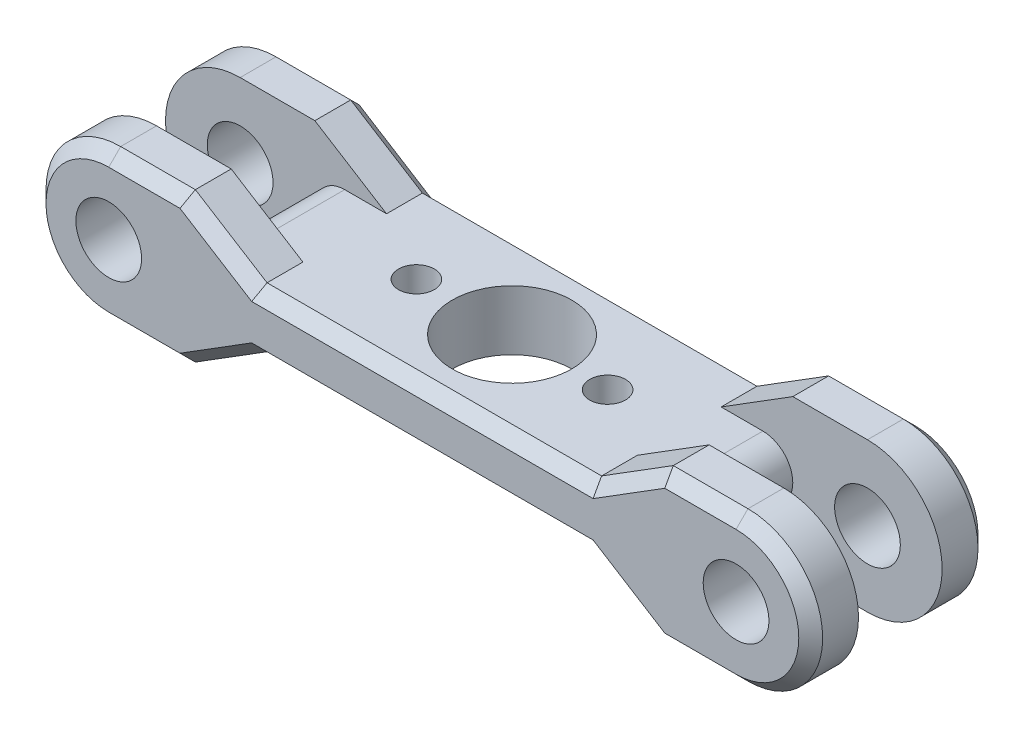
SolidWorks part; units mm, degrees
ref_plane "前视基准面" through (0, 0, 0) normal (0, 0, 1) x (1, 0, 0)
ref_plane "上视基准面" through (0, 0, 0) normal (0, 1, 0) x (1, 0, 0)
ref_plane "右视基准面" through (0, 0, 0) normal (1, 0, 0) x (0, 0, -1)
other "Configuration Table"
sketch "草图1" plane through (0, 0, 0) normal (0, 1, 0) x (1, 0, 0)
  line L1 (-20, -7.5) -> (20, -7.5)
  line L2 (-20, -7.5) -> (-20, 7.5)
  line L3 (-20, 7.5) -> (20, 7.5)
  line L4 (20, -7.5) -> (20, 7.5)
  line L5 (-20, -7.5) -> (20, 7.5) construction
  line L6 (-20, 7.5) -> (20, -7.5) construction
  point P0 (0, 0)
  dimension "D1" = 40
  dimension "D2" = 15
extrude "凸台-拉伸1" add sketch "草图1" along normal blind 5
sketch "草图2" plane through (0, 0, 0) normal (0, 1, 0) x (1, 0, 0)
  line L0 (-8, 0) -> (8, 0) construction
  circle A0 centre (0, 0) radius 5
  circle A1 centre (8, 0) radius 1.5
  circle A2 centre (-8, 0) radius 1.5
  point P5 (0, 0)
  dimension "D1" = 10
  dimension "D2" = 3
  dimension "D3" = 3
  dimension "D4" = 16
extrude "切除-拉伸1" cut sketch "草图2" against normal up to surface (5 mm away) from surface at 5 up to face at (0, 0, 0) starting at face at (0, 5, 0)
sketch "草图6" plane through (0, 0, 0) normal (0, 1, 0) x (1, 0, 0)
  line L0 (0, 7.5) -> (0, -7.5) construction
  line L1 (20, 7.5) -> (32.5, 7.5)
  line L2 (20, 7.5) -> (20, 3.5)
  line L3 (20, 3.5) -> (32.5, 3.5)
  line L4 (32.5, 7.5) -> (32.5, 3.5)
  line L5 (20, -7.5) -> (32.5, -7.5)
  line L6 (20, -7.5) -> (20, -3.5)
  line L7 (20, -3.5) -> (32.5, -3.5)
  line L8 (32.5, -7.5) -> (32.5, -3.5)
  line L9 (20, 7.5) -> (-20, 7.5) construction
  line L10 (-20, -7.5) -> (20, -7.5) construction
  line L11 (-20, -3.5) -> (-32.5, -3.5)
  line L12 (-32.5, -7.5) -> (-32.5, -3.5)
  line L13 (-20, -7.5) -> (-32.5, -7.5)
  line L14 (-20, -7.5) -> (-20, -3.5)
  line L15 (-20, 3.5) -> (-32.5, 3.5)
  line L16 (-32.5, 7.5) -> (-32.5, 3.5)
  line L17 (-20, 7.5) -> (-32.5, 7.5)
  line L18 (-20, 7.5) -> (-20, 3.5)
  dimension "D1" = 4
  dimension "D2" = 4
  dimension "D3" = 12.5
  dimension "D4" = 12.5
extrude "凸台-拉伸3" add sketch "草图6" along normal blind 8.75 and the other way blind 3.75
sketch "草图8" plane through (0, 0, 0) normal (0, 0, 1) x (1, 0, 0)
  line L0 (-20, -3.75) -> (-14, 0)
  line L1 (-20, 0) -> (20, 0) construction
  line L2 (-20, 8.75) -> (-14, 5)
  line L3 (-20, 5) -> (20, 5) construction
  line L4 (-14, 5) -> (-20, 5)
  line L5 (-20, 5) -> (-20, 8.75)
  line L6 (-20, -3.75) -> (-20, 0)
  line L7 (-20, 0) -> (-14, 0)
  line L8 (0, 0) -> (0, 5) construction
  line L9 (20, 0) -> (14, 0)
  line L10 (20, -3.75) -> (20, 0)
  line L11 (20, 5) -> (20, 8.75)
  line L12 (14, 5) -> (20, 5)
  line L13 (20, 8.75) -> (14, 5)
  line L14 (20, -3.75) -> (14, 0)
  dimension "D1" = 6
  dimension "D2" = 6
extrude "凸台-拉伸4" add sketch "草图8" against normal up to surface (4 mm away) from surface at 7.5 up to face at (-24.1667, 2.5, 3.5) starting at face at (0, 2.5, 7.5)
sketch "草图9" plane through (0, 0, 0) normal (0, 0, 1) x (1, 0, 0)
  line L3 (-14, 5) -> (-20, 8.75)
  line L4 (-20, 5) -> (-14, 5)
  line L5 (-20, 8.75) -> (-20, 5)
  line L6 (-14, 5) -> (-20, 8.75)
  line L7 (-20, 5) -> (-14, 5)
  line L8 (-20, 8.75) -> (-20, 5)
  line L9 (-20, -3.75) -> (-14, 0)
  line L10 (-14, 0) -> (-20, 0)
  line L11 (-20, 0) -> (-20, -3.75)
  line L12 (-20, -3.75) -> (-14, 0)
  line L13 (-14, 0) -> (-20, 0)
  line L14 (-20, 0) -> (-20, -3.75)
  line L15 (20, 5) -> (20, 8.75)
  line L16 (20, 8.75) -> (14, 5)
  line L17 (14, 5) -> (20, 5)
  line L18 (20, 5) -> (20, 8.75)
  line L19 (20, 8.75) -> (14, 5)
  line L20 (14, 5) -> (20, 5)
  line L21 (20, 0) -> (14, 0)
  line L22 (14, 0) -> (20, -3.75)
  line L23 (20, -3.75) -> (20, 0)
  line L24 (20, 0) -> (14, 0)
  line L25 (14, 0) -> (20, -3.75)
  line L26 (20, -3.75) -> (20, 0)
  dimension "D1" = 0
  dimension "D2" = 0
  dimension "D3" = 0
  dimension "D4" = 0
extrude "凸台-拉伸5" add sketch "草图9" along normal up to surface (4 mm away) from surface at -7.5 up to face at (-24.1667, 2.5, -3.5) starting at face at (0, 2.5, -7.5)
sketch "草图10" plane through (0, 0, 0) normal (0, 0, 1) x (1, 0, 0)
  line L0 (-32.5, 8.75) -> (-20, -3.75) construction
  line L1 (-32.5, -3.75) -> (-20, 8.75) construction
  line L2 (20, 8.75) -> (32.5, -3.75) construction
  line L3 (20, -3.75) -> (32.5, 8.75) construction
  line L4 (-32.5, 8.75) -> (-20, 8.75) construction
  line L5 (20, 8.75) -> (32.5, 8.75) construction
  line L6 (-32.5, -3.75) -> (-32.5, 2.5)
  line L7 (-32.5, 2.5) -> (-32.5, 8.75)
  line L8 (-32.5, 8.75) -> (-26.25, 8.75)
  line L9 (-32.5, -3.75) -> (-26.25, -3.75)
  line L10 (26.25, -3.75) -> (32.5, -3.75)
  line L11 (32.5, -3.75) -> (32.5, 2.5)
  line L12 (32.5, 2.5) -> (32.5, 8.75)
  line L13 (32.5, 8.75) -> (26.25, 8.75)
  arc A0 (-26.25, 8.75) -> (-26.25, -3.75) centre (-26.25, 2.5) ccw
  arc A1 (26.25, -3.75) -> (26.25, 8.75) centre (26.25, 2.5) ccw
  circle A2 centre (-26.25, 2.5) radius 2.75
  circle A3 centre (26.25, 2.5) radius 2.75
  dimension "D1" = 5.5
  dimension "D2" = 5.5
extrude "切除-拉伸3" cut sketch "草图10" against normal up to surface (15 mm away) from surface at 7.5 contours A0 L6 L9 | A0 L8 L7 | A3 | A1 L10 L11 | A1 L12 L13 | A2 up to face at (0, 2.5, -7.5) starting at face at (0, 2.5, 7.5)
sketch "草图11" plane through (0, 0, 0) normal (0, 0, 1) x (1, 0, 0)
  line L0 (-20, 5) -> (-15, 0) construction
  line L1 (-14, 0) -> (-20, 0) construction
  line L3 (-20, 0) -> (-15, 5) construction
  line L4 (-20, 5) -> (-14, 5) construction
  line L5 (-17.5, 0) -> (-20, 0)
  line L7 (-17.5, 5) -> (-20, 5)
  line L8 (-20, 5) -> (-20, 0)
  line L9 (-20, 0) -> (-20, 5) construction
  line L10 (0, 0) -> (0, 5) construction
  line L11 (5, 5) -> (-5, 5) construction
  line L12 (20, 0) -> (15, 5) construction
  line L13 (20, 5) -> (15, 0) construction
  line L14 (20, 5) -> (20, 0)
  line L15 (17.5, 5) -> (20, 5)
  line L16 (17.5, 0) -> (20, 0)
  arc A0 (-17.5, 5) -> (-17.5, 0) centre (-17.5, 2.5) ccw
  arc A1 (17.5, 5) -> (17.5, 0) centre (17.5, 2.5) cw
  dimension "D3" = 5
  dimension "D1" = 5
  dimension "D2" = 5
extrude "切除-拉伸4" cut sketch "草图11" along normal up to surface (7 mm away) from surface at -3.5 contours L15 A1 L14 | L14 A1 L16 | A0 L8 L5 | A0 L7 L8 up to face at (23.5, 2.5, 3.5) starting at face at (29, 2.5, -3.5)
chamfer "倒角1" distance 1 angle 45 24 edges at (-23.125, 8.75, -7.5) (-17, 6.875, -7.5) (-32.5, 2.5, -7.5) (-23.125, -3.75, -7.5) (-17, -1.875, -7.5) (0, 5, -7.5) (17, 6.875, -7.5) (23.125, 8.75, -7.5) (32.5, 2.5, -7.5) (23.125, -3.75, -7.5) (17, -1.875, -7.5) (0, 0, -7.5) (-23.125, -3.75, 7.5) (-32.5, 2.5, 7.5) (-23.125, 8.75, 7.5) (-17, 6.875, 7.5) (-17, -1.875, 7.5) (0, 0, 7.5) (17, -1.875, 7.5) (23.125, -3.75, 7.5) (32.5, 2.5, 7.5) (23.125, 8.75, 7.5) (17, 6.875, 7.5) (0, 5, 7.5)
